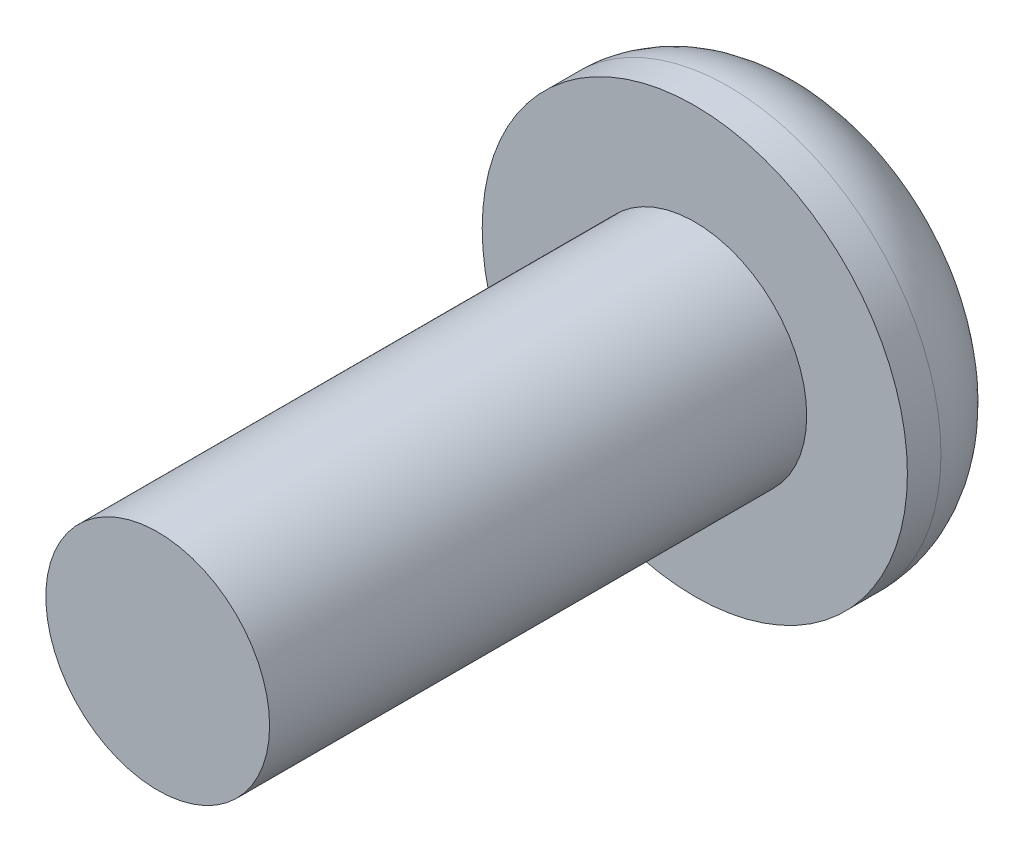
SolidWorks part; units mm, degrees
ref_plane "前视基准面" through (0, 0, 0) normal (0, 0, 1) x (1, 0, 0)
ref_plane "上视基准面" through (0, 0, 0) normal (0, 1, 0) x (1, 0, 0)
ref_plane "右视基准面" through (0, 0, 0) normal (1, 0, 0) x (0, 0, -1)
sketch "草图1" plane through (0, 0, 0) normal (0, 0, 1) x (1, 0, 0)
  circle A0 centre (0, 0) radius 2.5
extrude "凸台-拉伸1" add sketch "草图1" along normal blind 12
sketch "草图2" plane through (0, 0, 0) normal (0, 0, -1) x (-1, 0, 0)
  circle A0 centre (0, 0) radius 4.75
extrude "凸台-拉伸2" add sketch "草图2" along normal blind 2.75
fillet "圆角1" radius 2 1 edges at (-4.75, 0, -2.75)
